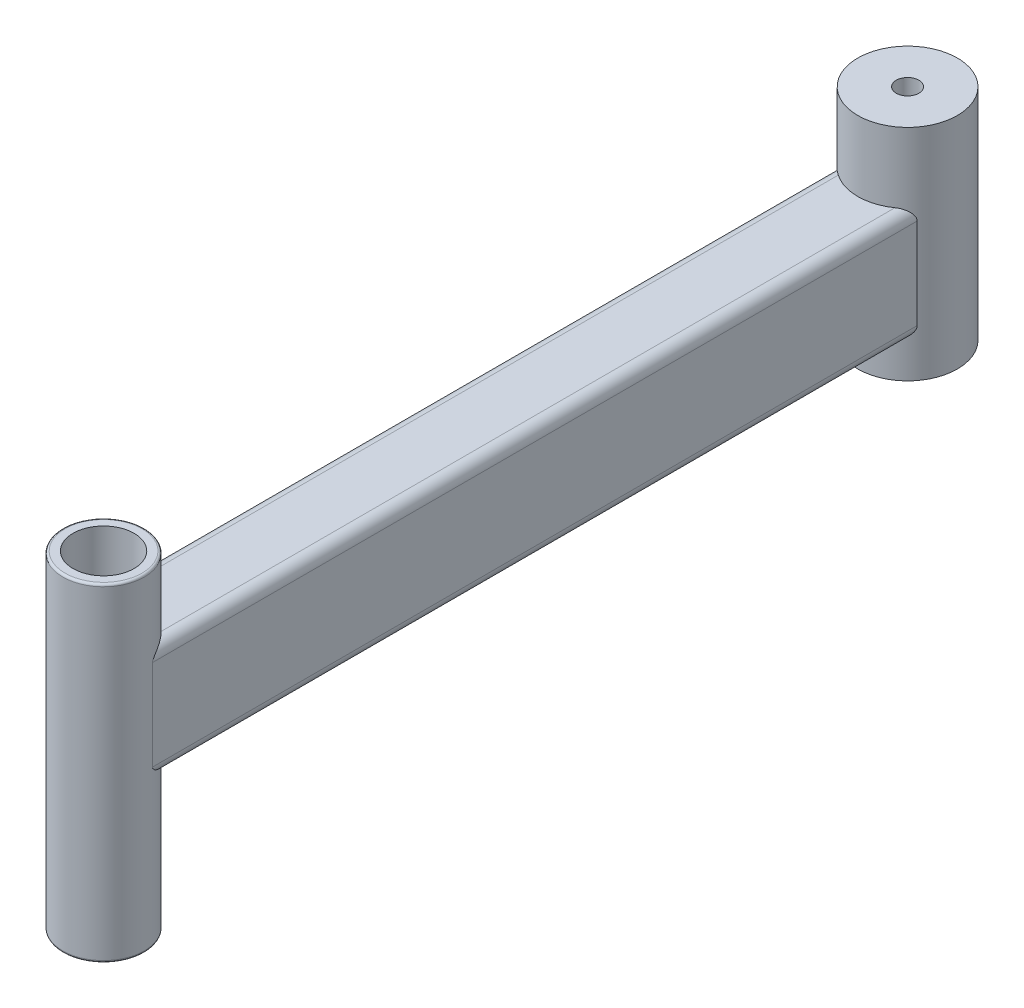
SolidWorks part; units mm, degrees
ref_plane "Front" through (0, 0, 0) normal (0, 0, 1) x (1, 0, 0)
ref_plane "Top" through (0, 0, 0) normal (0, 1, 0) x (1, 0, 0)
ref_plane "Right" through (0, 0, 0) normal (1, 0, 0) x (0, 0, -1)
sketch "Sketch1" plane through (0, 0, 0) normal (0, 1, 0) x (1, 0, 0)
  circle A0 centre (0, 0) radius 5.5
  circle A1 centre (0, 0) radius 22
  dimension "D1" = 11
extrude "Boss-Extrude1" add sketch "Sketch1" against normal blind 97 contours A1
sketch "Sketch2" plane through (0, 0, 0) normal (0, 1, 0) x (1, 0, 0)
  circle A0 centre (0, 0) radius 5
  dimension "D1" = 10
extrude "Cut-Extrude1" cut sketch "Sketch2" against normal through all
sketch "Sketch5" plane through (0, 0, 0) normal (0, 1, 0) x (1, 0, 0)
  line L0 (0, 0) -> (0, -22) construction
  circle A0 centre (0, 0) radius 22 construction
ref_plane "Plane1" through (0, 0, 22) normal (0, 0, 1) x (1, 0, 0)
sketch "Sketch6" plane through (0, 0, 22) normal (0, 0, 1) x (1, 0, 0)
  line L0 (0, 0) -> (0, -31) construction
  line L1 (-22, -31) -> (21.7592, -31) construction
  line L2 (-22, 0) -> (-22, -97) construction
  line L8 (-17.5, -31) -> (17.5, -31)
  line L9 (-17.5, -31) -> (-17.5, -81)
  line L10 (-17.5, -81) -> (17.5, -81)
  line L11 (17.5, -31) -> (17.5, -81)
extrude "Boss-Extrude2" add sketch "Sketch6" along normal offset from surface 332 and the other way blind 10 separate body contours L9 L10 L11 L8 up to face at (0, -97, 22)
sketch "Sketch7" plane through (0, 0, 0) normal (0, 1, 0) x (1, 0, 0)
  circle A0 centre (0, -355.176) radius 18
extrude "Boss-Extrude3" add sketch "Sketch7" against normal blind 145 separate body
sketch "Sketch8" plane through (0, 0, 0) normal (0, 1, 0) x (1, 0, 0)
  circle A0 centre (0, -355.176) radius 13.5
extrude "Cut-Extrude2" cut sketch "Sketch8" against normal through all
fillet "Fillet1" radius 5 4 edges at (-17.5, -81, 182.7836) (-17.5, -31, 182.7836) (17.5, -31, 182.7836) (17.5, -81, 182.7836)
fillet "Fillet2" radius 1 2 edges at (0, -145, 373.176) (0, 0, 373.176)
